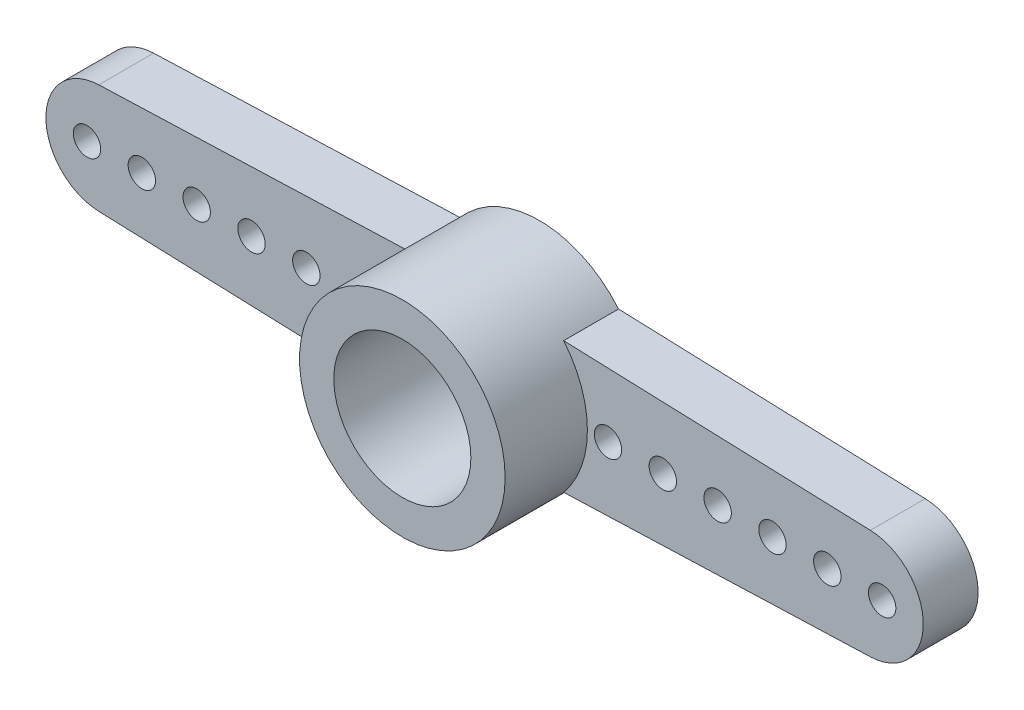
SolidWorks part; units mm, degrees
ref_plane "Спереди" through (0, 0, 0) normal (0, 0, 1) x (1, 0, 0)
ref_plane "Сверху" through (0, 0, 0) normal (0, 1, 0) x (1, 0, 0)
ref_plane "Справа" through (0, 0, 0) normal (1, 0, 0) x (0, 0, -1)
sketch "Эскиз1" plane through (0, 0, 0) normal (0, 0, 1) x (1, 0, 0)
  line L0 (0, 0) -> (-14, 0)
  line L1 (-14.0708, 1.9987) -> (0, 2.4974)
  line L2 (-14.0708, -1.9987) -> (0, -2.4974)
  line L4 (14.0708, -1.9987) -> (0, -2.4974)
  line L5 (14.0708, 1.9987) -> (0, 2.4974)
  circle A0 centre (0, 0) radius 3.75
  circle A1 centre (0, 0) radius 2.5
  arc A2 (-13.967, -1.9997) -> (-14.0708, 1.9987) centre (-14, 0) cw
  arc A3 (13.967, -1.9997) -> (14.0708, 1.9987) centre (14, 0) ccw
  dimension "D1" = 7.5
  dimension "D2" = 5
  dimension "D4" = 2
  dimension "D3" = 14
extrude "Бобышка-Вытянуть3" add sketch "Эскиз1" along normal blind 2
sketch "Эскиз2" plane through (0, 0, 2) normal (0, 0, 1) x (1, 0, 0)
  circle A0 centre (0, 0) radius 3.75
  circle A1 centre (0, 0) radius 2.5
  dimension "D1" = 5
extrude "Бобышка-Вытянуть5" add sketch "Эскиз2" along normal blind 3 separate body
sketch "Эскиз3" plane through (0, 0, 2) normal (0, 0, -1) x (-1, 0, 0)
  circle A0 centre (0, 0) radius 3.75
  circle A1 centre (0, 0) radius 2.5
extrude "Бобышка-Вытянуть6" add sketch "Эскиз3" along normal blind 2
sketch "Эскиз4" plane through (0, 0, 0) normal (0, 0, -1) x (-1, 0, 0)
  line L0 (-16, 0) -> (-14.5, 0)
  line L1 (-14.5, 0) -> (-12.5, 0)
  line L2 (-12.5, 0) -> (-10.5, 0)
  line L3 (-10.5, 0) -> (-8.5, 0)
  line L4 (-8.5, 0) -> (-6.5, 0)
  line L5 (-6.5, 0) -> (-4.5, 0)
  arc A0 (-14.0708, 1.9987) -> (-14.0708, -1.9987) centre (-14, 0) ccw construction
  circle A1 centre (-14.5, 0) radius 0.5
  circle A2 centre (-12.5, 0) radius 0.5
  circle A3 centre (-10.5, 0) radius 0.5
  circle A4 centre (-8.5, 0) radius 0.5
  circle A5 centre (-6.5, 0) radius 0.5
  circle A6 centre (-4.5, 0) radius 0.5
  circle A7 centre (4.5, 0) radius 0.5
  circle A8 centre (6.5, 0) radius 0.5
  circle A9 centre (8.5, 0) radius 0.5
  circle A10 centre (10.5, 0) radius 0.5
  circle A11 centre (12.5, 0) radius 0.5
  circle A12 centre (14.5, 0) radius 0.5
  dimension "D2" = 1
  dimension "D8" = 1
  dimension "D9" = 1
  dimension "D10" = 1
  dimension "D11" = 1
  dimension "D12" = 1
  dimension "D1" = 1.5
  dimension "D3" = 2
  dimension "D4" = 2
  dimension "D5" = 2
  dimension "D6" = 2
  dimension "D7" = 2
extrude "Вырез-Вытянуть1" cut sketch "Эскиз4" against normal blind 2
sketch "Эскиз5" plane through (0, 0, 0) normal (0, 0, -1) x (-1, 0, 0)
  circle A0 centre (0, 0) radius 2.5
extrude "Бобышка-Вытянуть7" add sketch "Эскиз5" against normal blind 1
sketch "Эскиз6" plane through (0, 0, 0) normal (0, 0, -1) x (-1, 0, 0)
  circle A0 centre (0, 0) radius 2.5
  dimension "D1" = 5
extrude "Вырез-Вытянуть2" cut sketch "Эскиз6" against normal blind 0.5
sketch "Эскиз7" plane through (0, 0, 0.5) normal (0, 0, -1) x (-1, 0, 0)
  circle A0 centre (0, 0) radius 1.25
  dimension "D1" = 2.5
extrude "Вырез-Вытянуть3" cut sketch "Эскиз7" against normal blind 5
sketch "Эскиз8" plane through (0, 0, 0.5) normal (0, 0, -1) x (-1, 0, 0)
  line L0 (-2.8252, -0.1999) -> (-2.8894, -0.2509)
sketch "Sketch1" plane through (0, 0, 0) normal (0, 0, -1) x (-1, 0, 0)
  line L4 (-14.0708, -1.9987) -> (-2.8855, -2.3951)
  line L5 (2.8855, -2.3951) -> (14.0708, -1.9987)
  line L6 (14.0708, 1.9987) -> (2.8855, 2.3951)
  line L7 (-2.8855, 2.3951) -> (-14.0708, 1.9987)
  line L8 (-14.0708, -1.9987) -> (-2.8855, -2.3951)
  line L9 (2.8855, -2.3951) -> (14.0708, -1.9987)
  line L10 (14.0708, 1.9987) -> (2.8855, 2.3951)
  line L11 (-2.8855, 2.3951) -> (-14.0708, 1.9987)
  arc A4 (-2.8855, -2.3951) -> (2.8855, -2.3951) centre (0, 0) ccw
  arc A5 (14.0708, -1.9987) -> (14.0708, 1.9987) centre (14, 0) ccw
  arc A6 (2.8855, 2.3951) -> (-2.8855, 2.3951) centre (0, 0) ccw
  arc A7 (-14.0708, 1.9987) -> (-14.0708, -1.9987) centre (-14, 0) ccw
  arc A8 (-2.8855, -2.3951) -> (2.8855, -2.3951) centre (0, 0) ccw
  arc A9 (14.0708, -1.9987) -> (14.0708, 1.9987) centre (14, 0) ccw
  arc A10 (2.8855, 2.3951) -> (-2.8855, 2.3951) centre (0, 0) ccw
  arc A11 (-14.0708, 1.9987) -> (-14.0708, -1.9987) centre (-14, 0) ccw
  dimension "D1" = 0
sketch "Sketch2" plane through (0, 0, 0) normal (0, 0, -1) x (-1, 0, 0)
  line L0 (-14.0708, -1.9987) -> (-2.8855, -2.3951) construction
  line L1 (2.8855, -2.3951) -> (14.0708, -1.9987) construction
  line L2 (14.0708, 1.9987) -> (2.8855, 2.3951) construction
  line L3 (-2.8855, 2.3951) -> (-14.0708, 1.9987) construction
  line L4 (-14.0708, -1.9987) -> (-2.8855, -2.3951)
  line L5 (2.8855, -2.3951) -> (14.0708, -1.9987)
  line L6 (14.0708, 1.9987) -> (2.8855, 2.3951)
  line L7 (-2.8855, 2.3951) -> (-14.0708, 1.9987)
  arc A0 (-2.8855, -2.3951) -> (2.8855, -2.3951) centre (0, 0) ccw construction
  arc A1 (14.0708, -1.9987) -> (14.0708, 1.9987) centre (14, 0) ccw construction
  arc A2 (2.8855, 2.3951) -> (-2.8855, 2.3951) centre (0, 0) ccw construction
  arc A3 (-14.0708, 1.9987) -> (-14.0708, -1.9987) centre (-14, 0) ccw construction
  circle A4 centre (0, 0) radius 2.5 construction
  arc A5 (-2.8855, -2.3951) -> (2.8855, -2.3951) centre (0, 0) ccw
  arc A6 (14.0708, -1.9987) -> (14.0708, 1.9987) centre (14, 0) ccw
  arc A7 (2.8855, 2.3951) -> (-2.8855, 2.3951) centre (0, 0) ccw
  arc A8 (-14.0708, 1.9987) -> (-14.0708, -1.9987) centre (-14, 0) ccw
  circle A9 centre (0, 0) radius 2.5
sketch "Sketch3" plane through (0, 0, 0.5) normal (0, 0, -1) x (-1, 0, 0)
  line L0 (-14.0708, -1.9987) -> (-2.8855, -2.3951) construction
  line L1 (2.8855, -2.3951) -> (14.0708, -1.9987) construction
  line L2 (14.0708, 1.9987) -> (2.8855, 2.3951) construction
  line L3 (-2.8855, 2.3951) -> (-14.0708, 1.9987) construction
  line L4 (-14.0708, -1.9987) -> (-2.8855, -2.3951)
  line L5 (2.8855, -2.3951) -> (14.0708, -1.9987)
  line L6 (14.0708, 1.9987) -> (2.8855, 2.3951)
  line L7 (-2.8855, 2.3951) -> (-14.0708, 1.9987)
  circle A0 centre (0, 0) radius 2.5 construction
  arc A1 (-2.8855, -2.3951) -> (2.8855, -2.3951) centre (0, 0) ccw construction
  arc A2 (14.0708, -1.9987) -> (14.0708, 1.9987) centre (14, 0) ccw construction
  arc A3 (2.8855, 2.3951) -> (-2.8855, 2.3951) centre (0, 0) ccw construction
  arc A4 (-14.0708, 1.9987) -> (-14.0708, -1.9987) centre (-14, 0) ccw construction
  circle A5 centre (0, 0) radius 2.5
  arc A6 (-2.8855, -2.3951) -> (2.8855, -2.3951) centre (0, 0) ccw
  arc A7 (14.0708, -1.9987) -> (14.0708, 1.9987) centre (14, 0) ccw
  arc A8 (2.8855, 2.3951) -> (-2.8855, 2.3951) centre (0, 0) ccw
  arc A9 (-14.0708, 1.9987) -> (-14.0708, -1.9987) centre (-14, 0) ccw
